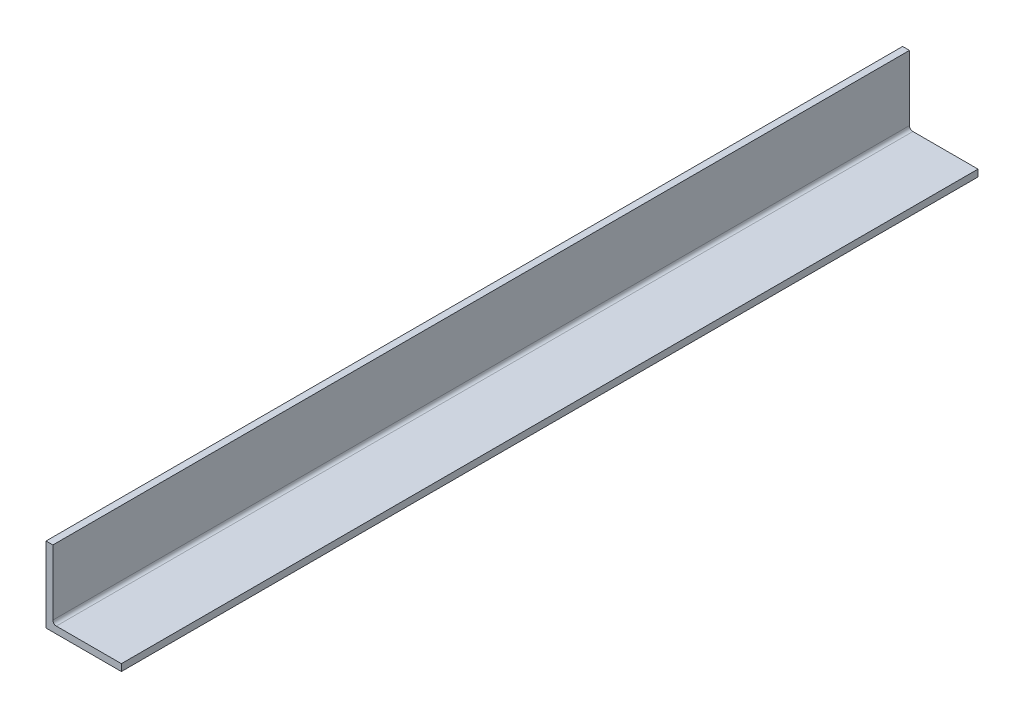
SolidWorks part; units mm, degrees
material "Aleación 1060"
ref_plane "Alzado" through (0, 0, 0) normal (0, 0, 1) x (1, 0, 0)
ref_plane "Planta" through (0, 0, 0) normal (0, 1, 0) x (1, 0, 0)
ref_plane "Vista lateral" through (0, 0, 0) normal (1, 0, 0) x (0, 0, -1)
sketch "Croquis1" plane through (0, 0, 0) normal (0, 0, 1) x (1, 0, 0)
  line L0 (0, 2) -> (0, 40)
  line L1 (2, 0) -> (40, 0)
  line L2 (-4, -4) -> (40, -4)
  line L3 (-4, -4) -> (-4, 40)
  line L4 (40, 0) -> (40, -4)
  line L5 (0, 40) -> (-4, 40)
  line L6 (0, 0) -> (0, 40) construction
  line L7 (0, 0) -> (40, 0) construction
  arc A0 (0, 2) -> (2, 0) centre (2, 2) ccw
  point P10 (0, 0)
  dimension "D2" = 2
  dimension "D1" = 4
extrude "Saliente-Extruir1" add sketch "Croquis1" along normal mid plane 500
